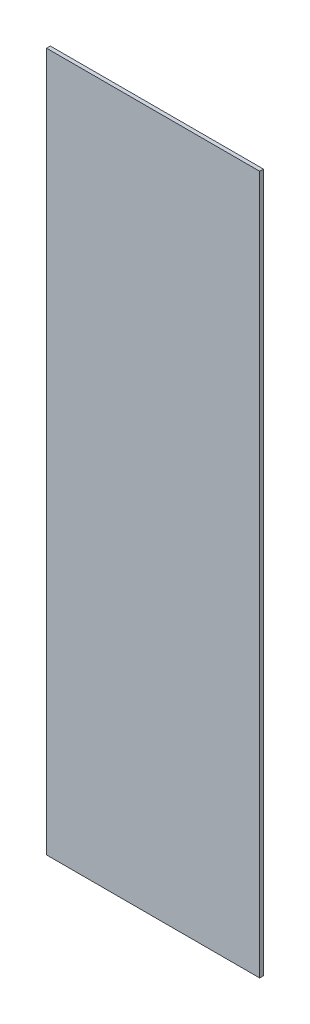
SolidWorks part; units mm, degrees
ref_plane "Front Plane" through (0, 0, 0) normal (0, 0, 1) x (1, 0, 0)
ref_plane "Top Plane" through (0, 0, 0) normal (0, 1, 0) x (1, 0, 0)
ref_plane "Right Plane" through (0, 0, 0) normal (1, 0, 0) x (0, 0, -1)
sketch "Sketch1" plane through (0, 0, 0) normal (0, 0, 1) x (1, 0, 0)
  line L1 (-84.5, 277) -> (84.5, 277)
  line L2 (-84.5, 277) -> (-84.5, -277)
  line L3 (-84.5, -277) -> (84.5, -277)
  line L4 (84.5, 277) -> (84.5, -277)
  line L5 (-84.5, 277) -> (84.5, -277) construction
  line L6 (-84.5, -277) -> (84.5, 277) construction
  point P0 (0, 0)
  dimension "D1" = 169
  dimension "D2" = 554
extrude "Boss-Extrude1" add sketch "Sketch1" along normal blind 3 contours L2 L3 L4 L1
